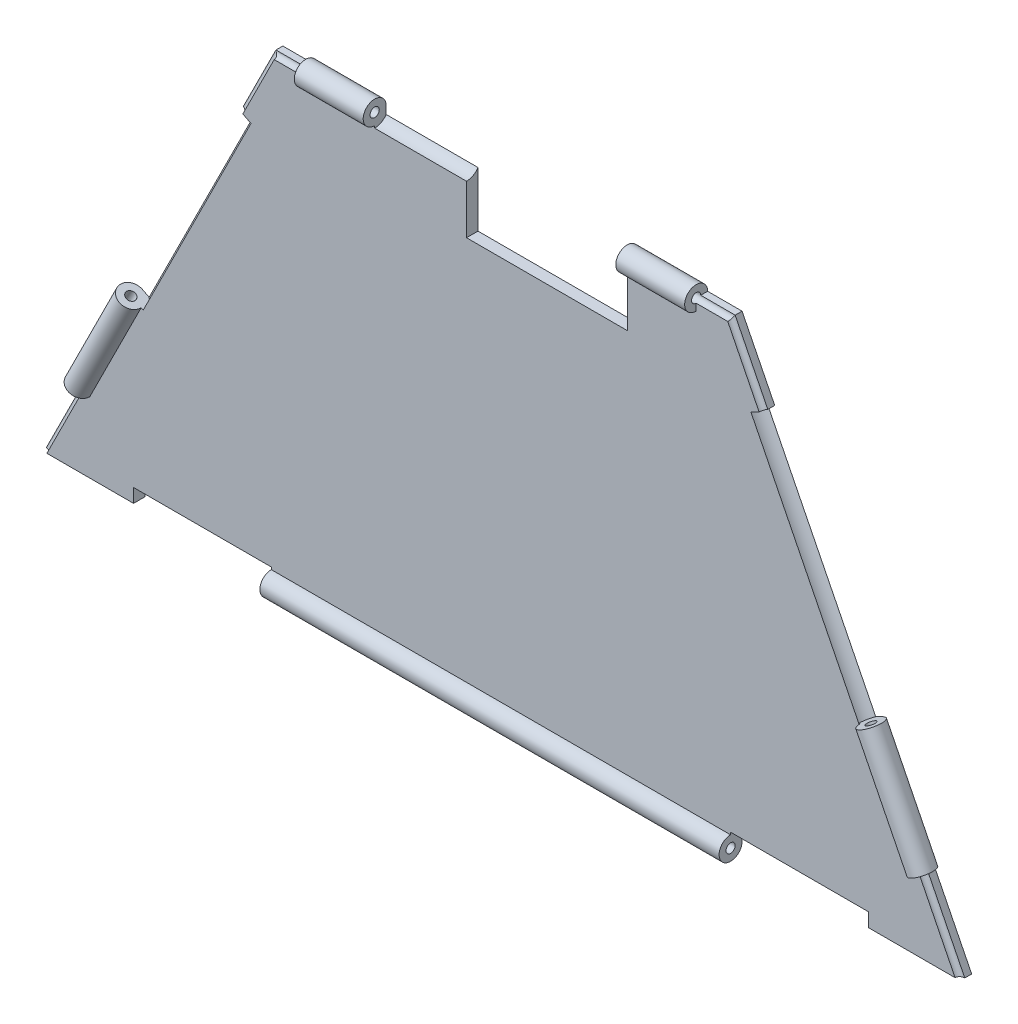
SolidWorks part; units mm, degrees
ref_plane "前视基准面" through (0, 0, 0) normal (0, 0, 1) x (1, 0, 0)
ref_plane "上视基准面" through (0, 0, 0) normal (0, 1, 0) x (1, 0, 0)
ref_plane "右视基准面" through (0, 0, 0) normal (1, 0, 0) x (0, 0, -1)
other "Configuration Table"
sketch "草图2" plane through (0, 65.305, 0) normal (0, 0, 1) x (1, 0, 0)
  line L28 (-200, 0) -> (-155, 0)
  line L29 (-155, 0) -> (-105, 0)
  line L30 (-105, 0) -> (105, 0)
  line L31 (105, 0) -> (155, 0)
  line L32 (155, 0) -> (200, 0)
  line L33 (200, 0) -> (195.8394, 8.3212)
  line L34 (195.8394, 8.3212) -> (151.118, 97.7639)
  line L35 (151.118, 97.7639) -> (100, 200)
  line L36 (100, 200) -> (50, 200)
  line L37 (50, 200) -> (-50, 200)
  line L38 (-50, 200) -> (-100, 200)
  line L39 (-100, 200) -> (-151.118, 97.7639)
  line L40 (-151.118, 97.7639) -> (-195.8394, 8.3212)
  line L41 (-195.8394, 8.3212) -> (-200, 0)
extrude "凸台-拉伸1" add sketch "草图2" along normal blind 5
sketch "草图3" plane through (0, 65.305, 0) normal (0, -1, 0) x (1, 0, 0)
  line L0 (-200, 2.5) -> (200, 2.5) construction
  line L1 (-100, 5) -> (100, 5)
  line L2 (-100, 5) -> (-100, 0)
  line L3 (-100, 0) -> (100, 0)
  line L4 (100, 5) -> (100, 0)
  line L5 (-200, 5) -> (-200, 0) construction
  line L6 (200, 5) -> (200, 0) construction
  line L7 (0, 5) -> (0, 0) construction
  line L8 (-200, 5) -> (200, 5) construction
  dimension "D1" = 200
  dimension "D2" = 5
sketch "草图4" plane through (-160, 145.305, 0) normal (-0.8944, 0.4472, 0) x (0, 0, 1)
  line L0 (2.5, 134.1641) -> (2.5, -89.4427) construction
  line L1 (5, 134.1641) -> (0, 134.1641) construction
  line L2 (5, -89.4427) -> (0, -89.4427) construction
  line L3 (5, 22.3607) -> (0, 22.3607) construction
  line L4 (5, 134.1641) -> (5, -89.4427) construction
  line L5 (0, 134.1641) -> (0, -89.4427) construction
  line L12 (0, -2.6393) -> (5, -2.6393)
  line L13 (0, -2.6393) -> (0, -52.6393)
  line L14 (0, -52.6393) -> (5, -52.6393)
  line L15 (5, -2.6393) -> (5, -52.6393)
  dimension "D1" = 50
  dimension "D2" = 25
sketch "草图7" plane through (0, 265.305, 0) normal (0, 1, 0) x (1, 0, 0)
  line L1 (-85, 1.5) -> (-55, 1.5)
  line L2 (-85, 1.5) -> (-85, -6.5)
  line L3 (-85, -6.5) -> (-55, -6.5)
  line L4 (-55, 1.5) -> (-55, -6.5)
  line L5 (-100, -2.5) -> (100, -2.5) construction
  line L6 (-100, -5) -> (-100, 0) construction
  line L7 (100, -5) -> (100, 0) construction
  line L8 (100, 0) -> (-100, 0) construction
  point P12 (0, 0)
  dimension "D1" = 30
  dimension "D2" = 55
  dimension "D3" = 8
sketch "草图9" plane through (0, 65.305, 5) normal (0, 0, 1) x (1, 0, 0)
  line L0 (-100, 200) -> (100, 200) construction
  line L1 (-85, 200) -> (-55, 200)
  line L2 (-85, 200) -> (-85, 195)
  line L3 (-85, 195) -> (-55, 195)
  line L4 (-55, 200) -> (-55, 195)
  dimension "D1" = 5
  dimension "D2" = 30
  dimension "D3" = 15
revolve "旋转1" add sketch "草图9" angle 360 about L1
sketch "草图10" plane through (-85, 65.305, 0) normal (-1, 0, 0) x (0, 0, 1)
  circle A0 centre (5, 200) radius 2
  dimension "D1" = 4
extrude "切除-拉伸3" cut sketch "草图10" against normal through all and the other way through all contours A0
mirror "镜向2" about plane through (0, 0, 0) normal (1, 0, 0) of "切除-拉伸3", "旋转1"
revolve "旋转2" add sketch "草图4" angle 360 about L15
sketch "草图11" plane through (-23.541, 18.223, 0) normal (-0.4472, -0.8944, 0) x (0.8944, -0.4472, 0)
  circle A0 centre (-178.8854, 5) radius 2
  dimension "D1" = 4
extrude "切除-拉伸4" cut sketch "草图11" against normal through all and the other way through all contours A0
sketch "草图12" plane through (-1.1803, 62.9444, 0) normal (0.4472, 0.8944, 0) x (0.8944, -0.4472, 0)
  circle A0 centre (-178.8854, -5) radius 6
  arc A2 (-178.8854, 0) -> (-173.8854, -5) centre (-178.8854, -5) ccw construction
  dimension "D1" = 12
extrude "切除-拉伸5" cut sketch "草图12" along normal blind 105
sketch "草图14" plane through (-55, 65.305, 0) normal (1, 0, 0) x (0, 0, -1)
  line L2 (-5, 195) -> (-5, 198)
  line L3 (-3, 200) -> (0, 200)
  line L5 (-3, 200) -> (0, 200)
  circle A0 centre (-5, 200) radius 6
  arc A2 (-3, 200) -> (-5, 198) centre (-5, 200) ccw
  arc A3 (0, 200) -> (-5, 195) centre (-5, 200) ccw
  line M6 (-5, 195) -> (-5, 198)
  arc M7 (-5, 198) -> (-3, 200) centre (-5, 200) cw
  line M8 (-3, 200) -> (0, 200)
  arc M9 (0, 200) -> (-5, 195) centre (-5, 200) ccw
  dimension "D2" = 12
  dimension "D1" = 0
extrude "切除-拉伸6" cut sketch "草图14" along normal up to surface (110 mm away) contours A0 M6 M9 M8 M7 | M9 M6 M7 M8 up to face at (55, 265.6675, 5.3624)
mirror "镜向3" about plane through (0, 0, 0) normal (1, 0, 0) of "切除-拉伸5", "切除-拉伸4", "旋转2"
revolve "旋转3" add sketch "草图3" angle 360 about L1
sketch "草图15" plane through (100, 65.305, 0) normal (1, 0, 0) x (0, 0, -1)
  circle A0 centre (-5, 0) radius 2
  dimension "D1" = 4
extrude "切除-拉伸7" cut sketch "草图15" against normal up to surface (200 mm away) contours A0 up to face at (-100, 64.9599, 5.3452)
sketch "草图16" plane through (100, 65.305, 0) normal (1, 0, 0) x (0, 0, -1)
  circle A0 centre (-5, 0) radius 6
  arc A1 (-5, 2) -> (-3, 0) centre (-5, 0) ccw construction
  dimension "D1" = 12
extrude "切除-拉伸8" cut sketch "草图16" along normal blind 60
sketch "草图17" plane through (-100, 65.305, 0) normal (-1, 0, 0) x (0, 0, 1)
  circle A0 centre (5, 0) radius 6
  arc A1 (0, 0) -> (5, 5) centre (5, 0) ccw construction
  dimension "D1" = 12
extrude "切除-拉伸9" cut sketch "草图17" along normal blind 60
scale "缩放比例1" scale about origin uniform scaling yes scale factor 0.5
sketch "草图19" plane through (0, 0, 0) normal (0, 0, -1) x (-1, 0, 0)
  line L0 (7.5, 130.9942) -> (7.5, 118.9942)
  line L1 (-27.5, 130.9942) -> (27.5, 130.9942) construction
  line L2 (7.5, 134.8011) -> (7.5, 130.1525) construction
  line L3 (7.5, 118.9942) -> (-27.5, 118.9942)
  line L4 (-27.5, 118.9942) -> (-27.5, 130.9942)
  line L5 (-27.5, 130.9942) -> (7.5, 130.9942)
extrude "切除-拉伸11" cut sketch "草图19" against normal blind 10
